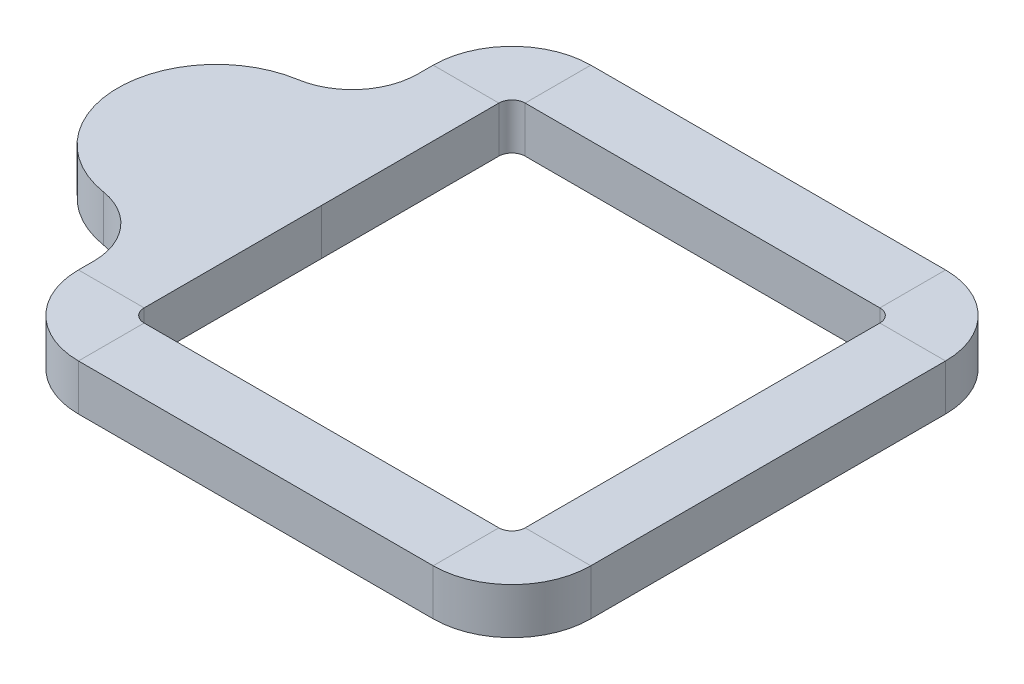
SolidWorks part; units mm, degrees
material "Резина"
ref_plane "Спереди" through (0, 0, 0) normal (0, 0, 1) x (1, 0, 0)
ref_plane "Сверху" through (0, 0, 0) normal (0, 1, 0) x (1, 0, 0)
ref_plane "Справа" through (0, 0, 0) normal (1, 0, 0) x (0, 0, -1)
sketch "Эскиз1" plane through (0.0734, 0, -1.827) normal (0, 0, -1) x (1, 0, 0)
  line L0 (-31, -10) -> (-31, -6) construction
  line L1 (-31, -10) -> (-31, -6) construction
  line L2 (-31, -9.75) -> (-31, -6.25)
  line L3 (-31, -9.75) -> (-36, -9.75)
  line L4 (-31, -6.25) -> (-36, -6.25)
  line L5 (-36, -9.75) -> (-36, -6.25)
  dimension "D1" = 3.5
  dimension "D2" = 0.25
  dimension "D3" = 5
ref_plane "Кольцо" through (0, 6.25, 0) normal (0, -1, 0) x (-1, 0, 0)
sketch "Эскиз2" plane through (0, 6.25, 0) normal (0, -1, 0) x (-1, 0, 0)
  line L0 (30.9266, 15.327) -> (30.9266, -11.673) construction
  line L1 (2.9266, 16.327) -> (29.9266, 16.327) construction
  line L2 (1.9266, 15.327) -> (1.9266, -11.673) construction
  line L3 (29.9266, -12.673) -> (2.9266, -12.673) construction
  line L4 (30.9266, 15.327) -> (30.9266, -11.673)
  line L5 (2.9266, 16.327) -> (29.9266, 16.327)
  line L6 (1.9266, 15.327) -> (1.9266, -11.673)
  line L7 (29.9266, -12.673) -> (2.9266, -12.673)
  arc A0 (30.9266, 15.327) -> (29.9266, 16.327) centre (29.9266, 15.327) ccw construction
  arc A1 (2.9266, 16.327) -> (1.9266, 15.327) centre (2.9266, 15.327) ccw construction
  arc A2 (1.9266, -11.673) -> (2.9266, -12.673) centre (2.9266, -11.673) ccw construction
  arc A3 (29.9266, -12.673) -> (30.9266, -11.673) centre (29.9266, -11.673) ccw construction
  arc A4 (30.9266, 15.327) -> (29.9266, 16.327) centre (29.9266, 15.327) ccw
  arc A5 (2.9266, 16.327) -> (1.9266, 15.327) centre (2.9266, 15.327) ccw
  arc A6 (1.9266, -11.673) -> (2.9266, -12.673) centre (2.9266, -11.673) ccw
  arc A7 (29.9266, -12.673) -> (30.9266, -11.673) centre (29.9266, -11.673) ccw
sweep "По траектории1" add profiles "Эскиз1" path "Эскиз2"
sketch "Эскиз3" plane through (0, 9.75, 0) normal (0, 1, 0) x (1, 0, 0)
  line L0 (-33.4266, 1.827) -> (-38.9266, 1.827) construction
  line L1 (-35.9266, 1.827) -> (-30.9266, 1.827) construction
  line L2 (-38.9266, 9.327) -> (-35.9266, 9.327)
  line L3 (-35.9266, 15.327) -> (-35.9266, 1.827) construction
  line L4 (-35.9266, 9.327) -> (-35.9266, -5.673)
  line L5 (-35.9266, -11.673) -> (-35.9266, 1.827) construction
  line L6 (-35.9266, -5.673) -> (-38.9266, -5.673)
  line L7 (-38.9266, -5.673) -> (-38.9266, 1.827) construction
  line L8 (-38.9266, 1.827) -> (-38.9266, 9.327) construction
  arc A0 (-38.9266, 9.327) -> (-38.9266, -5.673) centre (-38.9266, 1.827) ccw
  dimension "D1" = 3
  dimension "D2" = 15
extrude "Бобышка-Вытянуть1" add sketch "Эскиз3" against normal up to surface (3.5 mm away) up to face at (-32.8016, 6.25, -11.952)
fillet "Скругление1" radius 5 2 edges at (-35.9266, 8, -9.327) (-35.9266, 8, 5.673)
